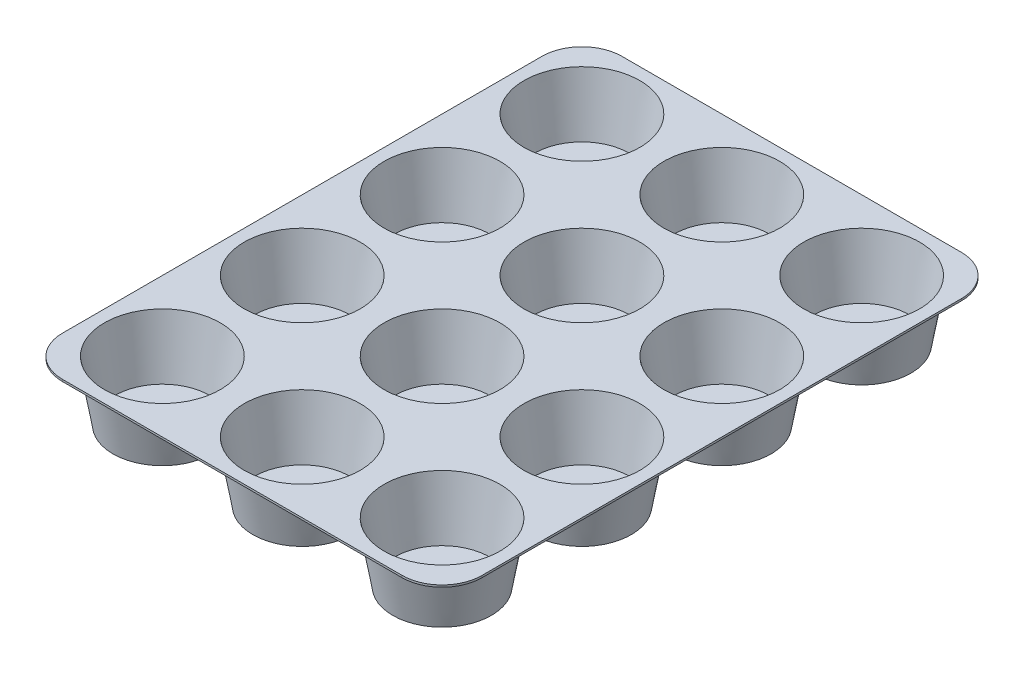
SolidWorks part; units mm, degrees
ref_plane "Front Plane" through (0, 0, 0) normal (0, 0, 1) x (1, 0, 0)
ref_plane "Top Plane" through (0, 0, 0) normal (0, 1, 0) x (1, 0, 0)
ref_plane "Right Plane" through (0, 0, 0) normal (1, 0, 0) x (0, 0, -1)
sketch "Sketch1" plane through (0, 0, 0) normal (0, 1, 0) x (1, 0, 0)
  line L1 (-133.35, 177.8) -> (133.35, 177.8)
  line L2 (-133.35, 177.8) -> (-133.35, -177.8)
  line L3 (-133.35, -177.8) -> (133.35, -177.8)
  line L4 (133.35, 177.8) -> (133.35, -177.8)
  line L5 (-133.35, 177.8) -> (133.35, -177.8) construction
  line L6 (-133.35, -177.8) -> (133.35, 177.8) construction
  point P0 (0, 0)
  dimension "D1" = 266.7
  dimension "D2" = 355.6
extrude "Boss-Extrude1" add sketch "Sketch1" along normal blind 1.27
sketch "Sketch2" plane through (0, 1.27, 0) normal (0, 1, 0) x (1, 0, 0)
  line L1 (-133.35, 177.8) -> (-133.35, -177.8) construction
  line L3 (133.35, 177.8) -> (-133.35, 177.8) construction
  circle A0 centre (-88.9, 133.35) radius 38.1
  point P2 (0, 0)
  point P7 (-88.125, 177.8)
  dimension "D1" = 76.2
  dimension "D2" = 44.45
  dimension "D3" = 44.45
extrude "Boss-Extrude3" add sketch "Sketch2" against normal blind 38.1 draft 10 contours A0
sketch "Sketch5" plane through (0, 1.27, 0) normal (0, 1, 0) x (1, 0, 0)
  line L0 (133.35, 177.8) -> (-133.35, 177.8) construction
  line L1 (-133.35, 177.8) -> (-133.35, -177.8) construction
  circle A0 centre (-88.9, 133.35) radius 36.83
  dimension "D1" = 73.66
  dimension "D2" = 44.45
  dimension "D3" = 44.45
extrude "Cut-Extrude2" cut sketch "Sketch5" against normal blind 36.83 draft 10 contours A0
pattern_linear "LPattern1" count 3 spacing 88.9 along (1, 0, 0) count 4 spacing 88.9 along (0, 0, 1) of "Cut-Extrude2", "Boss-Extrude3"
fillet "Fillet1" radius 25.4 4 edges at (-133.35, 0.635, 177.8) (133.35, 0.635, 177.8) (133.35, 0.635, -177.8) (-133.35, 0.635, -177.8)
